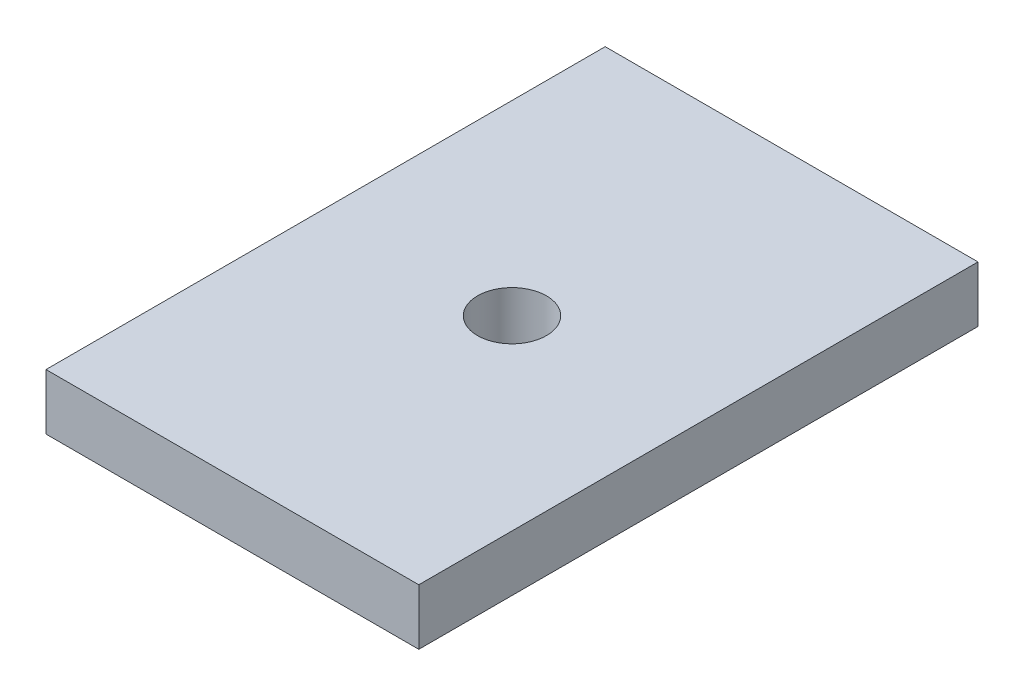
SolidWorks part; units mm, degrees
ref_plane "前视基准面" through (0, 0, 0) normal (0, 0, 1) x (1, 0, 0)
ref_plane "上视基准面" through (0, 0, 0) normal (0, 1, 0) x (1, 0, 0)
ref_plane "右视基准面" through (0, 0, 0) normal (1, 0, 0) x (0, 0, -1)
other "Configuration Table"
sketch "草图1" plane through (0, 0, 0) normal (0, 1, 0) x (1, 0, 0)
  line L1 (-10, 15) -> (10, 15)
  line L2 (-10, 15) -> (-10, -15)
  line L3 (-10, -15) -> (10, -15)
  line L4 (10, 15) -> (10, -15)
  line L5 (-10, 15) -> (10, -15) construction
  line L6 (-10, -15) -> (10, 15) construction
  point P0 (0, 0)
  dimension "D1" = 30
  dimension "D2" = 20
extrude "凸台-拉伸1" add sketch "草图1" along normal blind 3 contours L1 L4 L3 L2
sketch "草图2" plane through (0, 3, 0) normal (0, 1, 0) x (1, 0, 0)
  circle A0 centre (0, 0) radius 1.85
  dimension "D1" = 3.7
extrude "切除-拉伸1" cut sketch "草图2" against normal blind 3 contours A0
